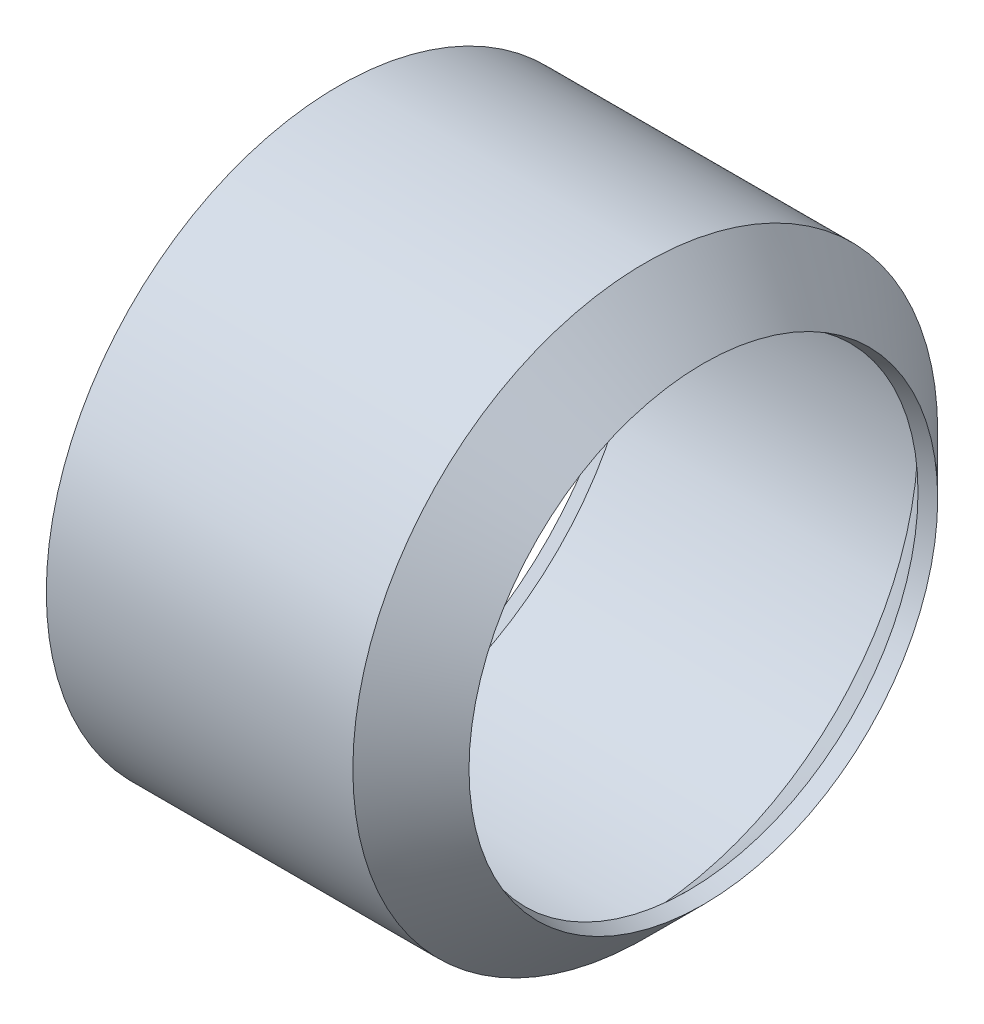
SolidWorks part; units mm, degrees
material "Silicon Rubber"
ref_plane "Front Plane" through (0, 0, 0) normal (0, 0, 1) x (1, 0, 0)
ref_plane "Top Plane" through (0, 0, 0) normal (0, 1, 0) x (1, 0, 0)
ref_plane "Right Plane" through (0, 0, 0) normal (1, 0, 0) x (0, 0, -1)
sketch "Sketch2" plane through (0, 0, 0) normal (0, 0, 1) x (1, 0, 0)
  line L0 (0, 0) -> (0, 19.05) construction
  line L11 (0, 19.05) -> (-20.32, 31.75)
  line L12 (81.28, 0) -> (81.28, 38.1) construction
  line L13 (-20.32, 44.45) -> (-7.62, 44.45)
  line L14 (-20.32, 44.45) -> (-20.32, 41.529)
  line L15 (-20.32, 41.529) -> (-7.62, 41.529)
  line L16 (-7.62, 41.529) -> (-7.62, 44.45)
  line L17 (-16.51, 41.529) -> (-16.51, 38.989)
  line L18 (-10.16, 25.4) -> (15.24, 25.4)
  line L22 (-20.32, 31.75) -> (-20.32, 44.45)
  line L23 (0, 0) -> (81.28, 0) construction
  line L25 (19.6574, 20.9826) -> (15.24, 25.4)
  line L27 (-20.32, 44.45) -> (0, 44.45)
  line L28 (-16.51, 38.989) -> (-11.43, 38.989)
  line L29 (-11.43, 38.989) -> (-11.43, 41.529)
  line L30 (81.28, 44.45) -> (0, 44.45)
  line L36 (-1.27, 44.45) -> (3.81, 44.45)
  line L37 (-1.27, 44.45) -> (-1.27, 41.91)
  line L38 (-1.27, 41.91) -> (3.81, 41.91)
  line L39 (3.81, 44.45) -> (3.81, 41.91)
  line L40 (0, 19.05) -> (12.7, 19.05)
  line L43 (81.28, 44.45) -> (81.28, 38.1)
  line L44 (12.7, 19.05) -> (81.28, 38.1)
  line L45 (-12.192, 26.67) -> (15.7661, 26.67)
  line L46 (15.7661, 26.67) -> (21.063, 21.3731)
  dimension "D1" = 19.05
  dimension "D2" = 20.32
  dimension "D4" = 45
  dimension "D5" = 31.75
  dimension "D15" = 25.4
  dimension "D3" = 12.7
  dimension "D6" = 68.58
  dimension "D7" = 38.1
  dimension "D8" = 41.529
  dimension "D9" = 5.08
  dimension "D10" = 2.54
  dimension "D11" = 3.81
  dimension "D12" = 6.35
  dimension "D13" = 5.08
  dimension "D14" = 2.54
  dimension "D16" = 12.7
  dimension "D18" = 1.27
  dimension "D19" = 44.45
  dimension "D20" = 1.27
  dimension "D17" = 25.4
revolve "Revolve2" add sketch "Sketch2" angle 360 about L23
